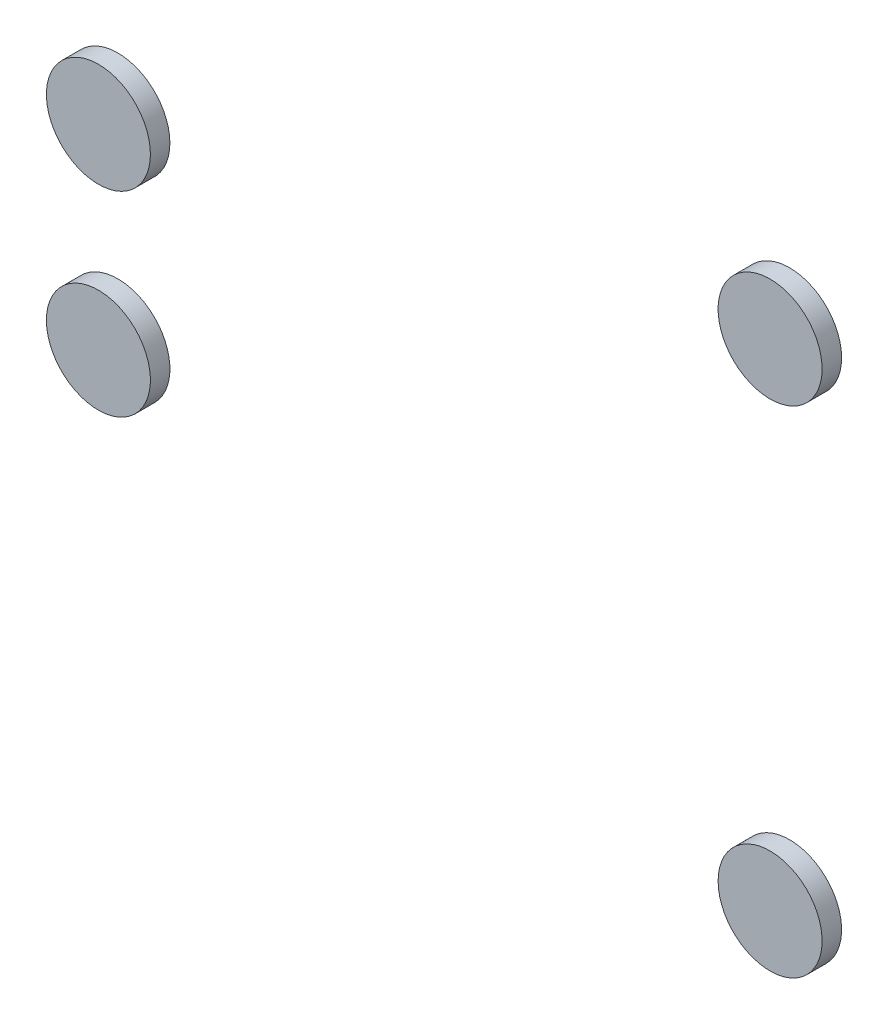
SolidWorks part; units mm, degrees
ref_plane "前视基准面" through (0, 0, 0) normal (0, 0, 1) x (1, 0, 0)
ref_plane "上视基准面" through (0, 0, 0) normal (0, 1, 0) x (1, 0, 0)
ref_plane "右视基准面" through (0, 0, 0) normal (1, 0, 0) x (0, 0, -1)
sketch "草图1" plane through (0, 0, 0) normal (0, 0, 1) x (1, 0, 0)
  line L0 (26.702, 0) -> (-26.2342, 0) construction
  line L1 (10, 0) -> (21, -19.0526) construction
  line L2 (-10, 0) -> (-30.6732, -7.5244)
  circle A4 centre (21, -19.0526) radius 4
  circle A5 centre (-30.6732, -7.5244) radius 4
  circle A6 centre (21, 19.0526) radius 4
  circle A7 centre (-30.6732, 7.5244) radius 4
  dimension "D1" = 8
  dimension "D2" = 22
  dimension "D3" = 60
  dimension "D4" = 20
extrude "凸台-拉伸1" add sketch "草图1" along normal blind 1.5 contours A4 | A6 | A7 | A5
